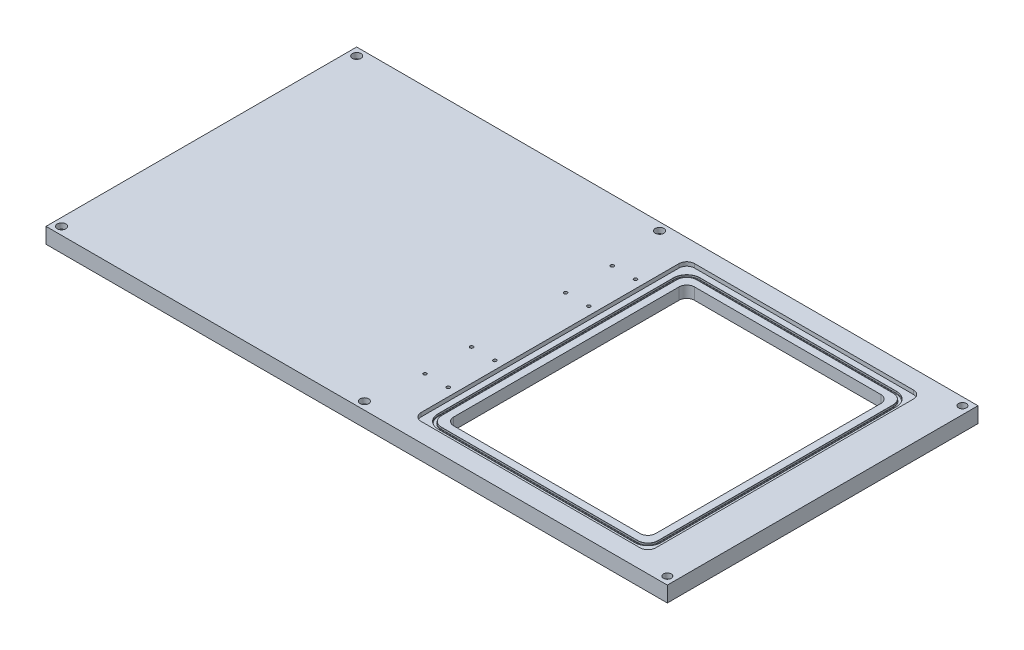
SolidWorks part; units mm, degrees
ref_plane "정면" through (0, 0, 0) normal (0, 0, 1) x (1, 0, 0)
ref_plane "윗면" through (0, 0, 0) normal (0, 1, 0) x (1, 0, 0)
ref_plane "우측면" through (0, 0, 0) normal (1, 0, 0) x (0, 0, -1)
sketch "스케치1" plane through (0, 0, 0) normal (0, 1, 0) x (1, 0, 0)
  line L1 (-400, 200) -> (400, 200)
  line L2 (-400, 200) -> (-400, -200)
  line L3 (-400, -200) -> (400, -200)
  line L4 (400, 200) -> (400, -200)
  line L5 (0, -200) -> (0, 200) construction
  line L6 (-400, 0) -> (400, 0) construction
  point P0 (0, 0)
  dimension "D1" = 400
  dimension "D2" = 800
extrude "보스-돌출1" add sketch "스케치1" along normal blind 20
sketch "스케치3" plane through (0, 20, 0) normal (0, 1, 0) x (1, 0, 0)
  line L0 (-400, -200) -> (400, -200) construction
  line L1 (49, 176) -> (351, 176)
  line L2 (49, 176) -> (49, -176)
  line L3 (49, -176) -> (351, -176)
  line L4 (351, 176) -> (351, -176)
  line L5 (200, -176) -> (200, 176) construction
  line L6 (49, 0) -> (351, 0) construction
  line L7 (400, -200) -> (400, 200) construction
  point P0 (200, 0)
  dimension "D1" = 302
  dimension "D2" = 352
  dimension "D3" = 24
  dimension "D4" = 49
extrude "컷-돌출1" cut sketch "스케치3" against normal blind 5
sketch "스케치4" plane through (0, 15, 0) normal (0, 1, 0) x (1, 0, 0)
  line L0 (400, -200) -> (400, 200) construction
  line L1 (73.5, 166.5) -> (326.5, 166.5) construction
  line L2 (58.5, 151.5) -> (58.5, -151.5) construction
  line L3 (73.5, -166.5) -> (326.5, -166.5) construction
  line L4 (341.5, 151.5) -> (341.5, -151.5) construction
  line L5 (-400, -200) -> (400, -200) construction
  line L7 (73.5, 168.55) -> (326.5, 168.55)
  line L8 (343.55, 151.5) -> (343.55, -151.5)
  line L9 (73.5, -168.55) -> (326.5, -168.55)
  line L10 (56.45, 151.5) -> (56.45, -151.5)
  line L11 (73.5, 164.45) -> (326.5, 164.45)
  line L12 (339.45, 151.5) -> (339.45, -151.5)
  line L13 (73.5, -164.45) -> (326.5, -164.45)
  line L14 (60.55, 151.5) -> (60.55, -151.5)
  arc A0 (326.5, -166.5) -> (341.5, -151.5) centre (326.5, -151.5) ccw construction
  arc A1 (58.5, -151.5) -> (73.5, -166.5) centre (73.5, -151.5) ccw construction
  arc A2 (73.5, 166.5) -> (58.5, 151.5) centre (73.5, 151.5) ccw construction
  arc A3 (326.5, 166.5) -> (341.5, 151.5) centre (326.5, 151.5) cw construction
  arc A4 (326.5, 168.55) -> (343.55, 151.5) centre (326.5, 151.5) cw
  arc A5 (326.5, -168.55) -> (343.55, -151.5) centre (326.5, -151.5) ccw
  arc A6 (56.45, -151.5) -> (73.5, -168.55) centre (73.5, -151.5) ccw
  arc A7 (73.5, 168.55) -> (56.45, 151.5) centre (73.5, 151.5) ccw
  arc A8 (326.5, 164.45) -> (339.45, 151.5) centre (326.5, 151.5) cw
  arc A9 (326.5, -164.45) -> (339.45, -151.5) centre (326.5, -151.5) ccw
  arc A10 (60.55, -151.5) -> (73.5, -164.45) centre (73.5, -151.5) ccw
  arc A11 (73.5, 164.45) -> (60.55, 151.5) centre (73.5, 151.5) ccw
  point P10 (341.5, -166.5)
  point P15 (58.5, 166.5)
  point P18 (341.5, 166.5)
  dimension "D5" = 15
  dimension "D1" = 58.5
  dimension "D2" = 283
  dimension "D3" = 33.5
  dimension "D4" = 333
  dimension "D6" = 2.05
  dimension "D7" = 2.05
extrude "컷-돌출2" cut sketch "스케치4" against normal blind 2.7
fillet "필렛1" radius 0.13 16 edges at (200, 15, -164.45) (335.657, 15, -160.657) (339.45, 15, 0) (335.657, 15, 160.657) (200, 15, 164.45) (64.343, 15, 160.657) (60.55, 15, 0) (200, 15, -168.55) (338.5562, 15, -163.5562) (343.55, 15, 0) (338.5562, 15, 163.5562) (200, 15, 168.55) (61.4438, 15, 163.5562) (56.45, 15, 0) (64.343, 15, -160.657) (61.4438, 15, -163.5562)
fillet "필렛2" radius 0.5 16 edges at (64.343, 12.3, -160.657) (200, 12.3, -164.45) (335.657, 12.3, -160.657) (339.45, 12.3, 0) (335.657, 12.3, 160.657) (200, 12.3, 164.45) (64.343, 12.3, 160.657) (61.4438, 12.3, -163.5562) (200, 12.3, -168.55) (338.5562, 12.3, -163.5562) (343.55, 12.3, 0) (338.5562, 12.3, 163.5562) (200, 12.3, 168.55) (61.4438, 12.3, 163.5562) (60.55, 12.3, 0) (56.45, 12.3, 0)
fillet "필렛3" radius 10 4 edges at (351, 17.5, 176) (49, 17.5, 176) (351, 17.5, -176) (49, 17.5, -176)
sketch "스케치6" plane through (0, 15, 0) normal (0, 1, 0) x (1, 0, 0)
  line L0 (-400, -200) -> (400, -200) construction
  line L1 (80, 155) -> (320, 155)
  line L2 (70, 145) -> (70, -145)
  line L3 (80, -155) -> (320, -155)
  line L4 (330, 145) -> (330, -145)
  line L5 (400, -200) -> (400, 200) construction
  arc A0 (70, -145) -> (80, -155) centre (80, -145) ccw
  arc A1 (320, -155) -> (330, -145) centre (320, -145) ccw
  arc A2 (320, 155) -> (330, 145) centre (320, 145) cw
  arc A3 (80, 155) -> (70, 145) centre (80, 145) ccw
  point P12 (330, -155)
  point P15 (330, 155)
  dimension "D4" = 10
  dimension "D1" = 45
  dimension "D2" = 310
  dimension "D3" = 70
  dimension "D5" = 260
extrude "컷-돌출3" cut sketch "스케치6" against normal through all
sketch "스케치10" plane through (0, 20, 0) normal (0, 1, 0) x (1, 0, 0)
  line L0 (-400, -200) -> (400, -200) construction
  line L1 (400, 200) -> (-400, 200) construction
  line L2 (-400, 200) -> (-400, -200) construction
  circle A0 centre (0, 190) radius 5.5
  circle A1 centre (-390, 190) radius 5.5
  circle A2 centre (-390, -190) radius 5.5
  circle A3 centre (0, -190) radius 5.5
  circle A4 centre (390, -190) radius 5
  circle A5 centre (390, 190) radius 5
  dimension "D5" = 11
  dimension "D6" = 10
  dimension "D7" = 10
  dimension "D1" = 10
  dimension "D2" = 10
  dimension "D3" = 10
  dimension "D4" = 390
  dimension "D8" = 390
extrude "컷-돌출4" cut sketch "스케치10" against normal blind 7
sketch "스케치11" plane through (0, 20, 0) normal (0, 1, 0) x (1, 0, 0)
  circle A0 centre (-390, 190) radius 3.25
  circle A1 centre (0, 190) radius 3.25
  circle A2 centre (0, -190) radius 3.25
  circle A3 centre (-390, -190) radius 3.25
  circle A4 centre (390, -190) radius 3.25
  circle A5 centre (390, 190) radius 3.25
  dimension "D1" = 6.5
extrude "컷-돌출5" cut sketch "스케치11" against normal through all
hole_wizard "M5 나사 구멍2" positions "스케치12" profile "스케치13" tap size "M5" standard "KS"
sketch "스케치12" plane through (0, 20, 0) normal (0, 1, 0) x (1, 0, 0)
  line L1 (-400, 200) -> (-400, -200) construction
  line L2 (-400, -200) -> (400, -200) construction
  point P0 (8.5, 120.5)
  point P2 (38.5, 120.5)
  point P4 (8.5, 60.5)
  point P6 (38.5, 60.5)
  point P8 (8.5, -60.5)
  point P10 (38.5, -60.5)
  point P12 (8.5, -120.5)
  point P14 (38.5, -120.5)
  dimension "D1" = 408.5
  dimension "D2" = 30
  dimension "D3" = 79.5
  dimension "D4" = 60
  dimension "D5" = 121
  dimension "D6" = 60
sketch "스케치13" plane through (8.5, 20, -120.5) normal (1, 0, 0) x (0, 0, 1)
  line L0 (0, 0) -> (0, 15.2618)
  line L1 (0, 15.2618) -> (2.1, 14)
  line L2 (2.1, 14) -> (2.1, 0)
  line L5 (2.1, 0) -> (0, 0)
  line L10 (0, 15.2618) -> (-2.1, 14) construction
  line L11 (0, -6.35) -> (0, 107.95) construction
  dimension "탭 드릴 지름" = 4.2
  dimension "탭 드릴 깊이" = 14
  dimension "드릴 각도" = 118
cosmetic thread "구멍 나사산5" parameters "D1"=10, "D2"=5
cosmetic thread "구멍 나사산6" parameters "D1"=10, "D2"=5
cosmetic thread "구멍 나사산7" parameters "D1"=10, "D2"=5
cosmetic thread "구멍 나사산8" parameters "D1"=10, "D2"=5
cosmetic thread "구멍 나사산9" parameters "D1"=10, "D2"=5
cosmetic thread "구멍 나사산10" parameters "D1"=10, "D2"=5
cosmetic thread "구멍 나사산11" parameters "D1"=10, "D2"=5
cosmetic thread "구멍 나사산12" parameters "D1"=10, "D2"=5
